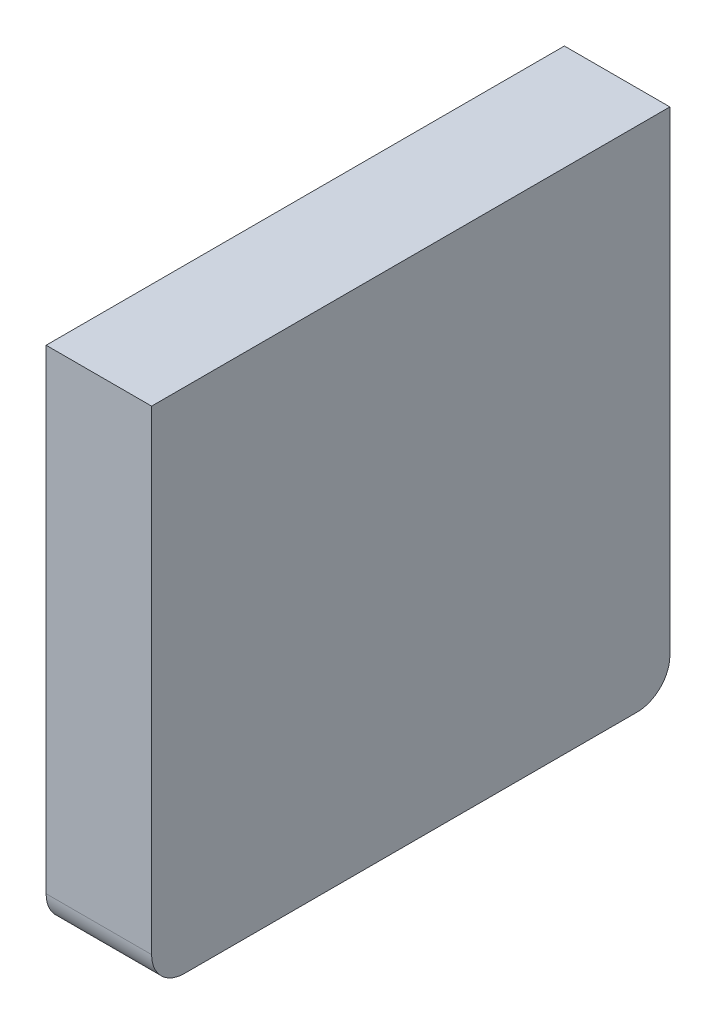
SolidWorks part; units mm, degrees
ref_plane "Front Plane" through (0, 0, 0) normal (0, 0, 1) x (1, 0, 0)
ref_plane "Top Plane" through (0, 0, 0) normal (0, 1, 0) x (1, 0, 0)
ref_plane "Right Plane" through (0, 0, 0) normal (1, 0, 0) x (0, 0, -1)
sketch "Sketch2" plane through (0, 0, 0) normal (0, 0, 1) x (1, 0, 0)
  line L1 (0, 0) -> (163.576, 0)
  line L2 (0, 0) -> (0, 787.4)
  line L3 (0, 787.4) -> (163.576, 787.4)
  line L4 (163.576, 0) -> (163.576, 787.4)
  dimension "D1" = 787.4
  dimension "D2" = 163.576
extrude "Boss-Extrude1" add sketch "Sketch2" along normal blind 803.656
fillet "Fillet1" radius 50.8 2 edges at (81.788, 0, 0) (81.788, 0, 803.656)
